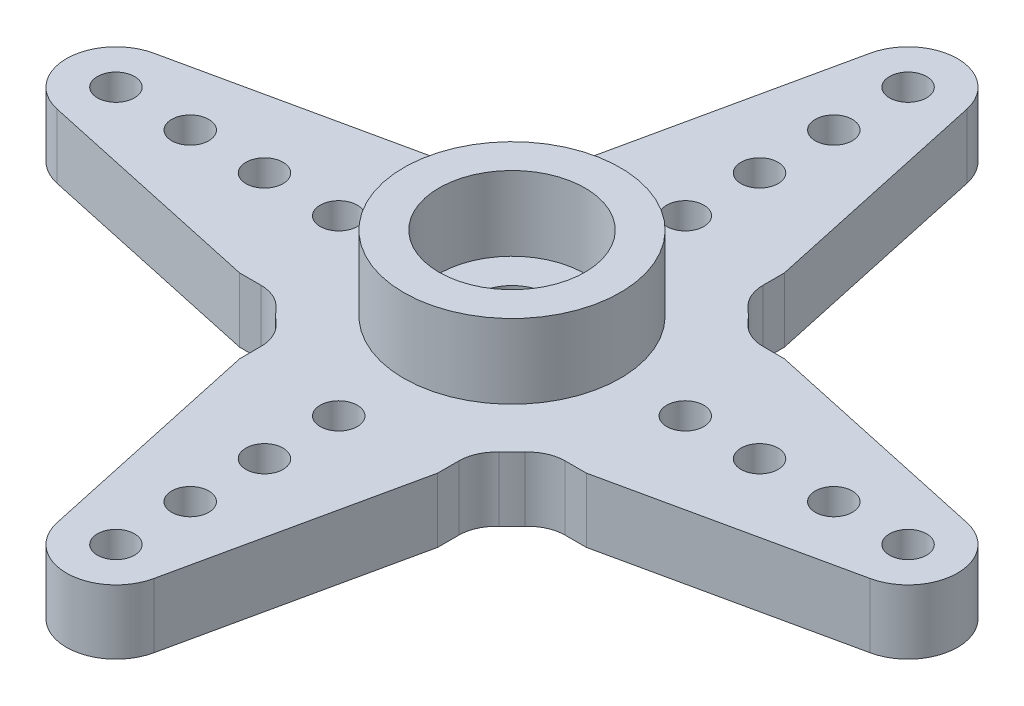
SolidWorks part; units mm, degrees
ref_plane "Alzado" through (0, 0, 0) normal (0, 0, 1) x (1, 0, 0)
ref_plane "Planta" through (0, 0, 0) normal (0, 1, 0) x (1, 0, 0)
ref_plane "Vista lateral" through (0, 0, 0) normal (1, 0, 0) x (0, 0, -1)
sketch "Croquis1" plane through (0, 0, 0) normal (0, 1, 0) x (1, 0, 0)
  line L0 (0, 0) -> (0, 16) construction
  line L1 (-4, 7) -> (-4, 6.1492)
  line L2 (0, 7) -> (-4, 7) construction
  line L3 (-4, 7) -> (-1.9545, 16.4242)
  line L4 (0, 0) -> (-4.773, 4.773) construction
  line L5 (4, 7) -> (4, 6.1492)
  line L6 (4, 7) -> (1.9545, 16.4242)
  line L7 (7, -4) -> (16.4242, -1.9545)
  line L8 (7, 4) -> (16.4242, 1.9545)
  line L9 (7, 4) -> (6.1492, 4)
  line L10 (7, -4) -> (6.1492, -4)
  line L11 (-4, -7) -> (-1.9545, -16.4242)
  line L12 (4, -7) -> (1.9545, -16.4242)
  line L13 (4, -7) -> (4, -6.1492)
  line L14 (-4, -7) -> (-4, -6.1492)
  line L15 (-7, 4) -> (-16.4242, 1.9545)
  line L16 (-7, -4) -> (-16.4242, -1.9545)
  line L17 (-7, -4) -> (-6.1492, -4)
  line L18 (-7, 4) -> (-6.1492, 4)
  circle A0 centre (0, 0) radius 6.75 construction
  circle A3 centre (0, 16) radius 0.75
  circle A4 centre (0, 13) radius 0.75
  circle A5 centre (0, 10) radius 0.75
  circle A6 centre (0, 7) radius 0.75
  arc A8 (1.9545, 16.4242) -> (-1.9545, 16.4242) centre (0, 16) ccw
  arc A9 (-4.773, 4.773) -> (-4.5, 5.0312) centre (0, 0) cw
  arc A10 (-4.5, 5.0312) -> (-4, 6.1492) centre (-5.5, 6.1492) ccw
  arc A11 (4.773, 4.773) -> (4.5, 5.0312) centre (0, 0) ccw
  arc A12 (4.5, 5.0312) -> (4, 6.1492) centre (5.5, 6.1492) cw
  circle A13 centre (16, 0) radius 0.75
  circle A14 centre (13, 0) radius 0.75
  arc A15 (16.4242, -1.9545) -> (16.4242, 1.9545) centre (16, 0) ccw
  circle A16 centre (10, 0) radius 0.75
  circle A17 centre (7, 0) radius 0.75
  arc A18 (5.0312, 4.5) -> (6.1492, 4) centre (6.1492, 5.5) ccw
  arc A19 (4.773, 4.773) -> (5.0312, 4.5) centre (0, 0) cw
  arc A20 (5.0312, -4.5) -> (6.1492, -4) centre (6.1492, -5.5) cw
  arc A21 (4.773, -4.773) -> (5.0312, -4.5) centre (0, 0) ccw
  circle A22 centre (0, -16) radius 0.75
  circle A23 centre (0, -13) radius 0.75
  arc A24 (-1.9545, -16.4242) -> (1.9545, -16.4242) centre (0, -16) ccw
  circle A25 centre (0, -10) radius 0.75
  circle A26 centre (0, -7) radius 0.75
  arc A27 (4.5, -5.0312) -> (4, -6.1492) centre (5.5, -6.1492) ccw
  arc A28 (4.773, -4.773) -> (4.5, -5.0312) centre (0, 0) cw
  arc A29 (-4.5, -5.0312) -> (-4, -6.1492) centre (-5.5, -6.1492) cw
  arc A30 (-4.773, -4.773) -> (-4.5, -5.0312) centre (0, 0) ccw
  circle A31 centre (-16, 0) radius 0.75
  circle A32 centre (-13, 0) radius 0.75
  arc A33 (-16.4242, 1.9545) -> (-16.4242, -1.9545) centre (-16, 0) ccw
  circle A34 centre (-10, 0) radius 0.75
  circle A35 centre (-7, 0) radius 0.75
  arc A36 (-5.0312, -4.5) -> (-6.1492, -4) centre (-6.1492, -5.5) ccw
  arc A37 (-4.773, -4.773) -> (-5.0312, -4.5) centre (0, 0) cw
  arc A38 (-5.0312, 4.5) -> (-6.1492, 4) centre (-6.1492, 5.5) cw
  arc A39 (-4.773, 4.773) -> (-5.0312, 4.5) centre (0, 0) ccw
  circle A40 centre (0, 0) radius 1.5
  point P16 (-4, 5.4371)
  point P88 (0, 0)
  dimension "D2" = 13.5
  dimension "D3" = 4
  dimension "D5" = 1.5
  dimension "D8" = 3
  dimension "D10" = 1.5
  dimension "D12" = 3
  dimension "D1" = 16
  dimension "D4" = 4
  dimension "D6" = 3
  dimension "D7" = 3
  dimension "D9" = 45
  dimension "D11" = 4
extrude "Saliente-Extruir1" add sketch "Croquis1" along normal blind 2.6 contours A9 A39 A38 L18 L15 A33 L16 L17 A36 A37 A30 A29 L14 L11 A24 L12 L13 A27 A28 A21 A20 L10 L7 A15 L8 L9 A18 A19 A11 A12 L5 L6 A8 L3 L1 A10 A40 A3 A4 A5 A6 A13 A14
sketch "Croquis2" plane through (0, 2.6, 0) normal (0, 1, 0) x (1, 0, 0)
  circle A0 centre (0, 0) radius 4.375
  circle A1 centre (0, 0) radius 2.95
  dimension "D1" = 5.9
  dimension "D2" = 8.75
extrude "Saliente-Extruir2" add sketch "Croquis2" along normal blind 3
